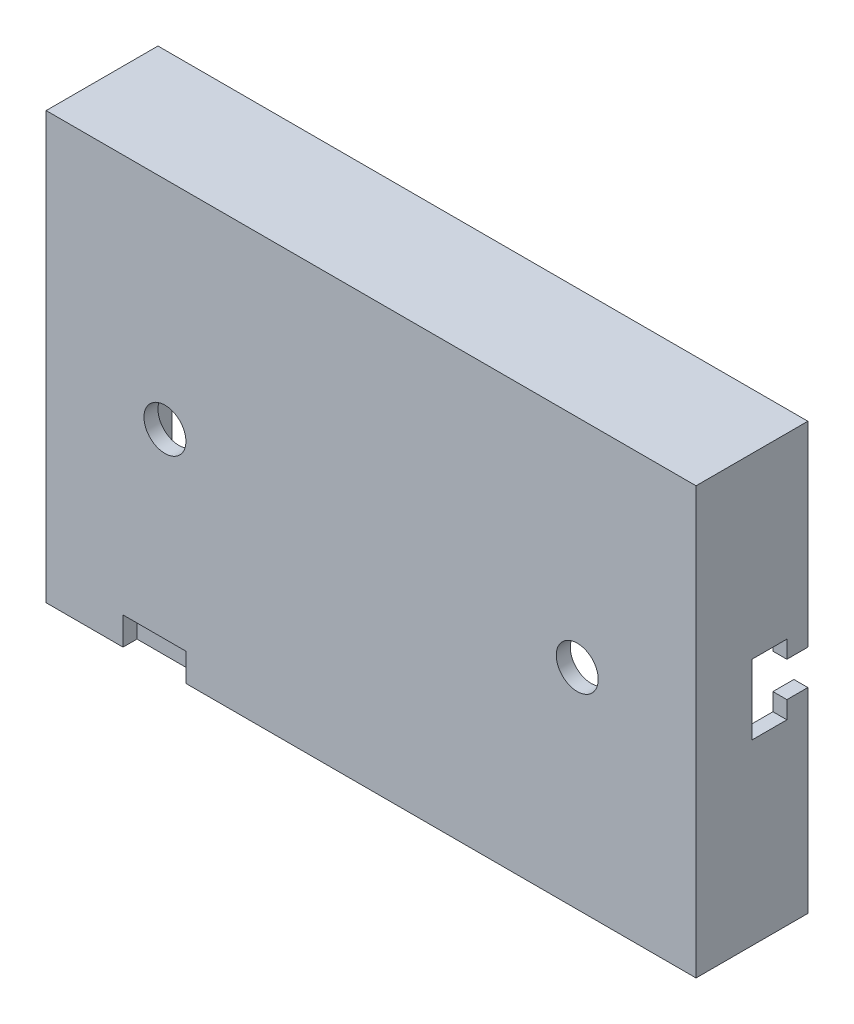
SolidWorks part; units mm, degrees
ref_plane "Plan de face" through (0, 0, 0) normal (0, 0, 1) x (1, 0, 0)
ref_plane "Plan de dessus" through (0, 0, 0) normal (0, 1, 0) x (1, 0, 0)
ref_plane "Plan de droite" through (0, 0, 0) normal (1, 0, 0) x (0, 0, -1)
sketch "Esquisse1" plane through (0, 0, 0) normal (0, 0, 1) x (1, 0, 0)
  line L1 (-40.3332, 23.1081) -> (48.6668, 23.1081)
  line L2 (-40.3332, 23.1081) -> (-40.3332, -33.8919)
  line L3 (-40.3332, -33.8919) -> (48.6668, -33.8919)
  line L4 (48.6668, 23.1081) -> (48.6668, -33.8919)
  dimension "D1" = 57
  dimension "D2" = 89
extrude "Boss.-Extru.1" add sketch "Esquisse1" along normal blind 2
sketch "Esquisse2" plane through (48.6668, 0, 0) normal (1, 0, 0) x (0, 0, -1)
  line L1 (-2, 23.1081) -> (14, 23.1081)
  line L2 (-2, 23.1081) -> (-2, -33.8919)
  line L3 (-2, -33.8919) -> (14, -33.8919)
  line L4 (14, 23.1081) -> (14, -33.8919)
  dimension "D1" = 16
  dimension "D2" = 57
extrude "Boss.-Extru.2" add sketch "Esquisse2" along normal blind 2
sketch "Esquisse3" plane through (-40.3332, 0, 0) normal (-1, 0, 0) x (0, 0, 1)
  line L1 (2, 23.1081) -> (-14, 23.1081)
  line L2 (2, 23.1081) -> (2, -33.8919)
  line L3 (2, -33.8919) -> (-14, -33.8919)
  line L4 (-14, 23.1081) -> (-14, -33.8919)
  dimension "D1" = 16
  dimension "D2" = 57
extrude "Boss.-Extru.3" add sketch "Esquisse3" along normal blind 2
sketch "Esquisse4" plane through (0, -33.8919, 0) normal (0, -1, 0) x (1, 0, 0)
  line L1 (-42.3332, 2) -> (50.6668, 2)
  line L2 (-42.3332, 2) -> (-42.3332, -14)
  line L3 (-42.3332, -14) -> (50.6668, -14)
  line L4 (50.6668, 2) -> (50.6668, -14)
extrude "Boss.-Extru.4" add sketch "Esquisse4" along normal blind 2
sketch "Esquisse5" plane through (0, 23.1081, 0) normal (0, 1, 0) x (1, 0, 0)
  line L1 (-42.3332, 14) -> (50.6668, 14)
  line L2 (-42.3332, 14) -> (-42.3332, -2)
  line L3 (-42.3332, -2) -> (50.6668, -2)
  line L4 (50.6668, 14) -> (50.6668, -2)
extrude "Boss.-Extru.5" add sketch "Esquisse5" along normal blind 2
sketch "Esquisse6" plane through (0, 0, 0) normal (0, 0, -1) x (-1, 0, 0)
  circle A0 centre (25.3332, -5.8919) radius 3
extrude "Enlèv. mat.-Extru.1" cut sketch "Esquisse6" against normal blind 2 contours A0
sketch "Esquisse7" plane through (0, 0, 0) normal (0, 0, -1) x (-1, 0, 0)
  circle A0 centre (-33.6668, -5.8919) radius 3
extrude "Enlèv. mat.-Extru.2" cut sketch "Esquisse7" against normal blind 2
sketch "Esquisse9" plane through (0, 0, -14) normal (0, 0, -1) x (-1, 0, 0)
  line L0 (-50.6668, 25.1081) -> (-50.6668, -5.3919) construction
  line L1 (-50.6668, -35.8919) -> (-50.6668, 25.1081) construction
sketch "Esquisse11" plane through (50.6668, 0, 0) normal (1, 0, 0) x (0, 0, -1)
  line L0 (14, -5.3919) -> (11, -5.3945) construction
  line L1 (6, -0.3945) -> (11, -0.3945)
  line L2 (6, -0.3945) -> (6, -10.3945)
  line L3 (6, -10.3945) -> (11, -10.3945)
  line L4 (11, -0.3945) -> (11, -10.3945)
  line L7 (14, -35.8919) -> (14, 25.1081) construction
  dimension "D1" = 10
  dimension "D2" = 5
extrude "Enlèv. mat.-Extru.3" cut sketch "Esquisse11" against normal blind 2
sketch "Esquisse12" plane through (50.6668, 0, 0) normal (1, 0, 0) x (0, 0, -1)
  line L0 (11, -0.3945) -> (14, -0.3945) construction
  line L1 (14, 25.1081) -> (14, -5.3919) construction
  line L2 (14, -0.3945) -> (14, -10.3945) construction
  line L3 (14, -35.8919) -> (14, 25.1081) construction
  line L4 (14, -10.3945) -> (11, -10.3945) construction
  line L5 (11, -10.3945) -> (11, -5.3945) construction
  line L6 (11, -10.3945) -> (11, -0.3945) construction
  line L7 (14, -5.3945) -> (11, -5.3945) construction
sketch "Esquisse13" plane through (50.6668, 0, 0) normal (1, 0, 0) x (0, 0, -1)
  line L0 (11, -10.3945) -> (11, -0.3945) construction
  line L1 (11, -2.8945) -> (14, -2.8945)
  line L2 (11, -2.8945) -> (11, -7.8945)
  line L3 (11, -7.8945) -> (14, -7.8945)
  line L4 (14, -2.8945) -> (14, -7.8945)
  line L5 (14, -0.3945) -> (14, -10.3945) construction
  line L6 (14, -2.8945) -> (14, -5.3945) construction
  line L7 (14, -5.3945) -> (14, -7.8945) construction
  dimension "D1" = 5
extrude "Enlèv. mat.-Extru.4" cut sketch "Esquisse13" against normal blind 2
sketch "Esquisse14" plane through (0, 0, 2) normal (0, 0, 1) x (1, 0, 0)
  line L0 (-42.3332, -35.8919) -> (-31.3332, -35.8919) construction
  line L1 (50.6668, -35.8919) -> (-42.3332, -35.8919) construction
  line L3 (-31.3332, -35.8919) -> (-22.3332, -35.8919)
  line L4 (-31.3332, -35.8919) -> (-31.3332, -31.8919)
  line L5 (-31.3332, -31.8919) -> (-22.3332, -31.8919)
  line L6 (-22.3332, -35.8919) -> (-22.3332, -31.8919)
  point P8 (-20.153, -35.8919)
  dimension "D1" = 9
  dimension "D2" = 4
extrude "Enlèv. mat.-Extru.7" cut sketch "Esquisse14" against normal blind 2
